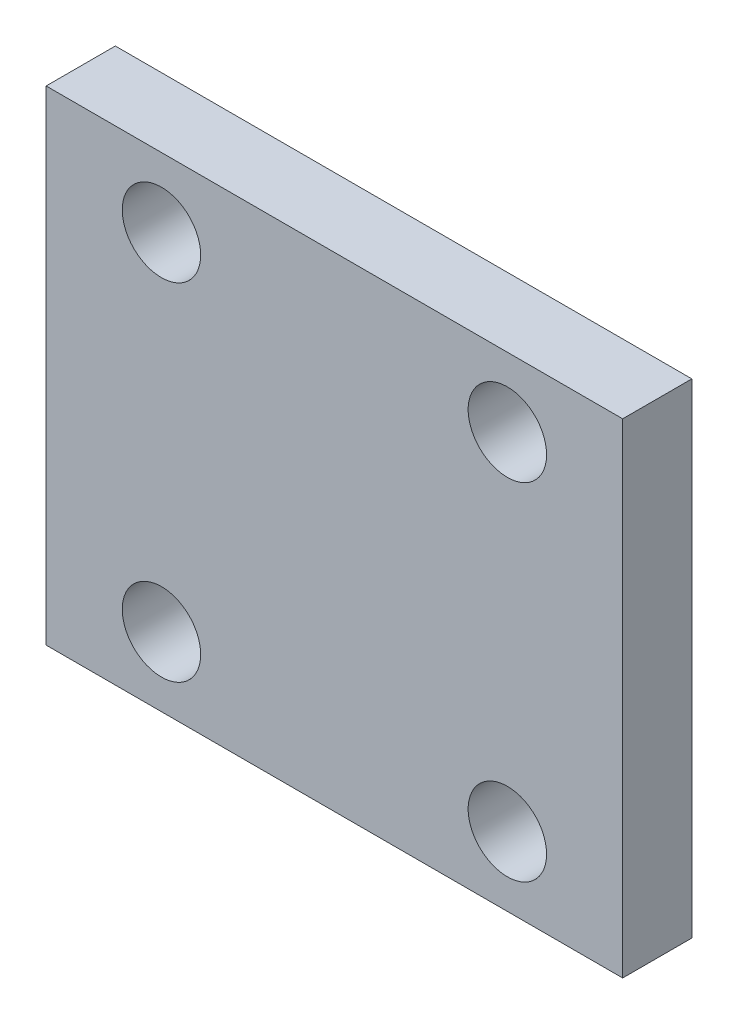
SolidWorks part; units mm, degrees
ref_plane "前视基准面" through (0, 0, 0) normal (0, 0, 1) x (1, 0, 0)
ref_plane "上视基准面" through (0, 0, 0) normal (0, 1, 0) x (1, 0, 0)
ref_plane "右视基准面" through (0, 0, 0) normal (1, 0, 0) x (0, 0, -1)
other "Configuration Table"
sketch "草图1" plane through (0, 0, 0) normal (0, 0, 1) x (1, 0, 0)
  line L1 (0, 0) -> (25, 0)
  line L2 (0, 0) -> (0, 21)
  line L3 (0, 21) -> (25, 21)
  line L4 (25, 0) -> (25, 21)
  dimension "D1" = 25
  dimension "D2" = 21
extrude "凸台-拉伸1" add sketch "草图1" along normal blind 3
sketch "草图2" plane through (0, 0, 3) normal (0, 0, 1) x (1, 0, 0)
  line L1 (5, 3) -> (20, 3) construction
  line L2 (5, 3) -> (5, 18) construction
  line L3 (5, 18) -> (20, 18) construction
  line L4 (20, 3) -> (20, 18) construction
  line L5 (5, 3) -> (20, 18) construction
  line L6 (5, 18) -> (20, 3) construction
  circle A0 centre (20, 18) radius 1.7
  circle A1 centre (5, 18) radius 1.7
  circle A2 centre (5, 3) radius 1.7
  circle A3 centre (20, 3) radius 1.7
  point P0 (12.5, 10.5)
  dimension "D3" = 3.4
  dimension "D1" = 15
  dimension "D2" = 15
extrude "切除-拉伸1" cut sketch "草图2" against normal up to next
ref_plane "基准面1" through (12.5, 0, 0) normal (-1, 0, 0) x (0, 0, 1)
